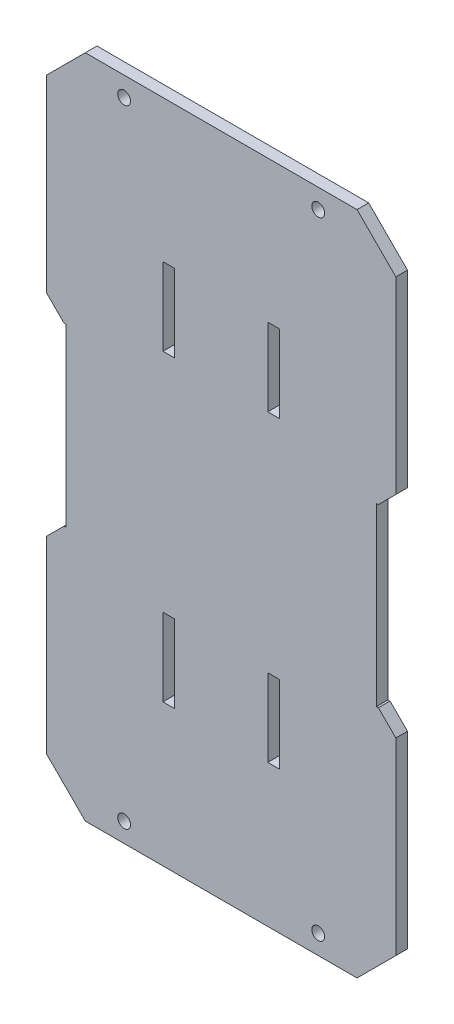
SolidWorks part; units mm, degrees
ref_plane "Front Plane" through (0, 0, 0) normal (0, 0, 1) x (1, 0, 0)
ref_plane "Top Plane" through (0, 0, 0) normal (0, 1, 0) x (1, 0, 0)
ref_plane "Right Plane" through (0, 0, 0) normal (1, 0, 0) x (0, 0, -1)
sketch "Sketch1" plane through (0, 0, 0) normal (0, 0, 1) x (1, 0, 0)
  line L0 (0.5528, 47.78) -> (20.5528, 47.78) construction
  line L1 (-49.4472, 47.78) -> (-29.4472, 47.78) construction
  line L2 (-49.4472, 47.78) -> (-49.4472, -25.43) construction
  line L3 (-49.4472, -25.43) -> (-29.4472, -25.43) construction
  line L4 (-29.4472, 47.78) -> (-29.4472, -25.43) construction
  line L5 (0.5528, 47.78) -> (0.5528, -25.43) construction
  line L6 (0.5528, -25.43) -> (20.5528, -25.43) construction
  line L7 (20.5528, 47.78) -> (20.5528, -25.43) construction
  line L8 (0.5528, -30.43) -> (20.5528, -30.43) construction
  line L9 (-49.4472, -30.43) -> (-29.4472, -30.43) construction
  line L10 (-49.4472, -30.43) -> (-49.4472, -103.64) construction
  line L11 (-49.4472, -103.64) -> (-29.4472, -103.64) construction
  line L12 (-29.4472, -30.43) -> (-29.4472, -103.64) construction
  line L13 (0.5528, -30.43) -> (0.5528, -103.64) construction
  line L14 (0.5528, -103.64) -> (20.5528, -103.64) construction
  line L15 (20.5528, -30.43) -> (20.5528, -103.64) construction
  line L16 (-59.4472, 47.78) -> (-49.4472, 57.78)
  line L17 (-49.4472, 57.78) -> (20.5528, 57.78)
  line L18 (-59.4472, 47.78) -> (-59.4472, -0.7692)
  line L19 (-49.4472, -113.64) -> (20.5528, -113.64)
  line L21 (20.5528, 57.78) -> (30.5528, 47.78)
  line L22 (30.5528, -103.64) -> (20.5528, -113.64)
  line L23 (-59.4472, -103.64) -> (-49.4472, -113.64)
  line L24 (-54.4472, 52.78) -> (-54.4472, -62.7481) construction
  line L25 (-54.4472, -50.5907) -> (-54.9472, -50.5907)
  line L26 (-54.4472, -50.5907) -> (-54.4472, -5.2692)
  line L27 (-54.4472, -5.2692) -> (-54.9472, -5.2692)
  line L29 (-59.4472, -0.7692) -> (-54.9472, -5.2692)
  line L30 (-54.9472, -50.5907) -> (-59.4472, -55.0907)
  line L31 (-59.4472, -55.0907) -> (-59.4472, -103.64)
  line L32 (-14.4472, 57.78) -> (-14.4472, -113.64) construction
  line L33 (30.5528, -55.0907) -> (30.5528, -103.64)
  line L34 (25.5528, -50.5907) -> (26.0528, -50.5907)
  line L35 (26.0528, -50.5907) -> (30.5528, -55.0907)
  line L36 (25.5528, -50.5907) -> (25.5528, -5.2692)
  line L37 (30.5528, 47.78) -> (30.5528, -0.7692)
  line L38 (30.5528, -0.7692) -> (26.0528, -5.2692)
  line L39 (25.5528, -5.2692) -> (26.0528, -5.2692)
  line L40 (-39.4472, 57.78) -> (-39.4472, 52.78) construction
  line L41 (10.5528, 57.78) -> (10.5528, 52.78) construction
  line L42 (-54.4472, -27.93) -> (25.5528, -27.93) construction
  line L43 (-29.4472, 11.175) -> (0.5528, 11.175) construction
  line L45 (-29.4472, 21.175) -> (-29.4472, 1.175)
  line L47 (-26.4472, 21.175) -> (-26.4472, 1.175)
  line L49 (0.5528, 21.175) -> (0.5528, 1.175)
  line L51 (-2.4472, 21.175) -> (-2.4472, 1.175)
  line L60 (-29.4472, 1.175) -> (-26.4472, 1.175)
  line L61 (-29.4472, 21.175) -> (-26.4472, 21.175)
  line L62 (-2.4472, 21.175) -> (0.5528, 21.175)
  line L63 (-2.4472, 1.175) -> (0.5528, 1.175)
  line L64 (-29.4472, 21.175) -> (0.5528, 21.175) construction
  line L65 (-2.4472, -77.035) -> (0.5528, -77.035)
  line L66 (-29.4472, 1.175) -> (0.5528, 1.175) construction
  line L67 (0.5528, -77.035) -> (0.5528, -57.035)
  line L68 (-2.4472, -57.035) -> (0.5528, -57.035)
  line L69 (-2.4472, -77.035) -> (-2.4472, -57.035)
  line L70 (-29.4472, -77.035) -> (-26.4472, -77.035)
  line L71 (-26.4472, -77.035) -> (-26.4472, -57.035)
  line L72 (-29.4472, -57.035) -> (-26.4472, -57.035)
  line L73 (-29.4472, -77.035) -> (-29.4472, -57.035)
  circle A0 centre (-39.4472, 52.78) radius 1.65
  circle A1 centre (10.5528, 52.78) radius 1.65
  circle A2 centre (10.5528, -108.64) radius 1.65
  circle A3 centre (-39.4472, -108.64) radius 1.65
  point P16 (-59.4472, 57.78)
  point P17 (30.5528, -113.64)
  point P18 (-59.4472, -113.64)
  point P19 (30.5528, 57.78)
  point P28 (-59.4472, -27.93)
  point P35 (-59.4472, -5.2692)
  point P37 (-59.4472, -50.5907)
  point P41 (-54.6972, -50.5907)
  point P43 (25.8028, -50.5907)
  dimension "D17" = 3.3
  dimension "D23" = 3.3
  dimension "D1" = 30
  dimension "D2" = 30
  dimension "D3" = 20
  dimension "D4" = 20
  dimension "D5" = 20
  dimension "D6" = 20
  dimension "D7" = 20
  dimension "D8" = 10
  dimension "D9" = 10
  dimension "D10" = 20
  dimension "D11" = 73.21
  dimension "D12" = 73.21
  dimension "D13" = 73.21
  dimension "D14" = 73.21
  dimension "D15" = 5
  dimension "D16" = 10
  dimension "D18" = 20
  dimension "D24" = 10
  dimension "D25" = 10
extrude "Boss-Extrude2" add sketch "Sketch1" along normal blind 3
